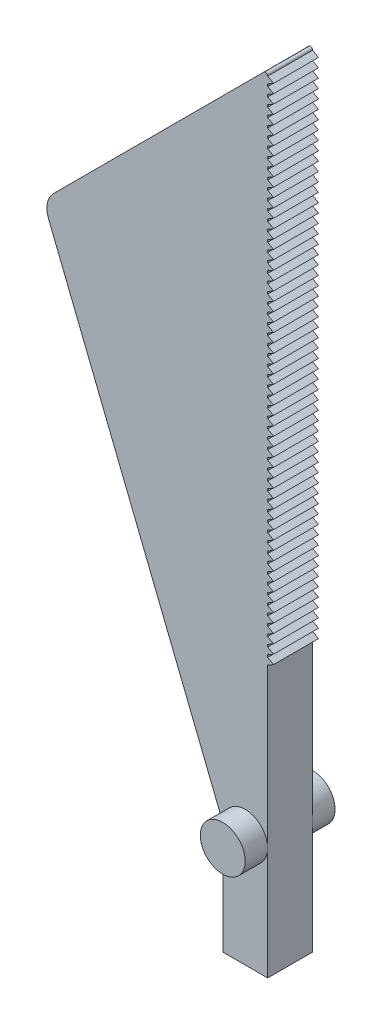
SolidWorks part; units mm, degrees
ref_plane "Front Plane" through (0, 0, 0) normal (0, 0, 1) x (1, 0, 0)
ref_plane "Top Plane" through (0, 0, 0) normal (0, 1, 0) x (1, 0, 0)
ref_plane "Right Plane" through (0, 0, 0) normal (1, 0, 0) x (0, 0, -1)
sketch "Sketch1" plane through (0, 0, 0) normal (0, 0, 1) x (1, 0, 0)
  circle A0 centre (0, 0) radius 2.54
  dimension "D1" = 5.08
extrude "Boss-Extrude1" add sketch "Sketch1" along normal mid plane 10.16
sketch "Sketch2" plane through (0, 0, 0) normal (0, 0, 1) x (1, 0, 0)
  line L0 (0, 0) -> (0, 76.2) construction
  line L1 (2.54, 0) -> (2.54, 75.5868)
  line L2 (2.1064, 75.7664) -> (-21.6757, 51.9843)
  line L4 (-2.54, -12.7) -> (2.54, -12.7)
  line L5 (2.54, -12.7) -> (2.54, 0)
  line L6 (-22.238, 49.2449) -> (-2.54, 0)
  line L7 (-2.54, 0) -> (-2.54, -12.7)
  circle A0 centre (0, 0) radius 2.54 construction
  arc A1 (-21.6757, 51.9843) -> (-22.238, 49.2449) centre (-19.8796, 50.1883) ccw
  arc A2 (2.54, 75.5868) -> (2.1064, 75.7664) centre (2.286, 75.5868) ccw
  point P19 (-22.86, 50.8)
  point P22 (2.54, 76.2)
  dimension "D4" = 2.54
  dimension "D5" = 0.254
  dimension "D1" = 76.2
  dimension "D2" = 25.4
  dimension "D3" = 50.8
  dimension "D6" = 12.7
extrude "Boss-Extrude2" add sketch "Sketch2" along normal mid plane 5.08
sketch "Sketch3" plane through (0, 0, 0) normal (0, 0, 1) x (1, 0, 0)
  line L0 (2.54, 75.5868) -> (3.1999, 75.2058)
  line L1 (3.1999, 75.2058) -> (2.54, 74.8248)
  line L2 (2.54, 0) -> (2.54, 75.5868) construction
  line L3 (2.54, 74.8248) -> (2.54, 75.5868)
  line L4 (2.54, 74.5708) -> (3.1999, 74.1898)
  line L5 (3.1999, 74.1898) -> (2.54, 73.8088)
  line L6 (2.54, 73.8088) -> (2.54, 74.5708)
  line L7 (2.54, 73.5548) -> (3.1999, 73.1738)
  line L8 (3.1999, 73.1738) -> (2.54, 72.7928)
  line L9 (2.54, 72.7928) -> (2.54, 73.5548)
  line L10 (2.54, 72.5388) -> (3.1999, 72.1578)
  line L11 (3.1999, 72.1578) -> (2.54, 71.7768)
  line L12 (2.54, 71.7768) -> (2.54, 72.5388)
  line L13 (2.54, 71.5228) -> (3.1999, 71.1418)
  line L14 (3.1999, 71.1418) -> (2.54, 70.7608)
  line L15 (2.54, 70.7608) -> (2.54, 71.5228)
  line L16 (2.54, 70.5068) -> (3.1999, 70.1258)
  line L17 (3.1999, 70.1258) -> (2.54, 69.7448)
  line L18 (2.54, 69.7448) -> (2.54, 70.5068)
  line L19 (2.54, 69.4908) -> (3.1999, 69.1098)
  line L20 (3.1999, 69.1098) -> (2.54, 68.7288)
  line L21 (2.54, 68.7288) -> (2.54, 69.4908)
  line L22 (2.54, 68.4748) -> (3.1999, 68.0938)
  line L23 (3.1999, 68.0938) -> (2.54, 67.7128)
  line L24 (2.54, 67.7128) -> (2.54, 68.4748)
  line L25 (2.54, 67.4588) -> (3.1999, 67.0778)
  line L26 (3.1999, 67.0778) -> (2.54, 66.6968)
  line L27 (2.54, 66.6968) -> (2.54, 67.4588)
  line L28 (2.54, 66.4428) -> (3.1999, 66.0618)
  line L29 (3.1999, 66.0618) -> (2.54, 65.6808)
  line L30 (2.54, 65.6808) -> (2.54, 66.4428)
  line L31 (2.54, 65.4268) -> (3.1999, 65.0458)
  line L32 (3.1999, 65.0458) -> (2.54, 64.6648)
  line L33 (2.54, 64.6648) -> (2.54, 65.4268)
  line L34 (2.54, 64.4108) -> (3.1999, 64.0298)
  line L35 (3.1999, 64.0298) -> (2.54, 63.6488)
  line L36 (2.54, 63.6488) -> (2.54, 64.4108)
  line L37 (2.54, 63.3948) -> (3.1999, 63.0138)
  line L38 (3.1999, 63.0138) -> (2.54, 62.6328)
  line L39 (2.54, 62.6328) -> (2.54, 63.3948)
  line L40 (2.54, 62.3788) -> (3.1999, 61.9978)
  line L41 (3.1999, 61.9978) -> (2.54, 61.6168)
  line L42 (2.54, 61.6168) -> (2.54, 62.3788)
  line L43 (2.54, 61.3628) -> (3.1999, 60.9818)
  line L44 (3.1999, 60.9818) -> (2.54, 60.6008)
  line L45 (2.54, 60.6008) -> (2.54, 61.3628)
  line L46 (2.54, 60.3468) -> (3.1999, 59.9658)
  line L47 (3.1999, 59.9658) -> (2.54, 59.5848)
  line L48 (2.54, 59.5848) -> (2.54, 60.3468)
  line L49 (2.54, 59.3308) -> (3.1999, 58.9498)
  line L50 (3.1999, 58.9498) -> (2.54, 58.5688)
  line L51 (2.54, 58.5688) -> (2.54, 59.3308)
  line L52 (2.54, 58.3148) -> (3.1999, 57.9338)
  line L53 (3.1999, 57.9338) -> (2.54, 57.5528)
  line L54 (2.54, 57.5528) -> (2.54, 58.3148)
  line L55 (2.54, 57.2988) -> (3.1999, 56.9178)
  line L56 (3.1999, 56.9178) -> (2.54, 56.5368)
  line L57 (2.54, 56.5368) -> (2.54, 57.2988)
  line L58 (2.54, 56.2828) -> (3.1999, 55.9018)
  line L59 (3.1999, 55.9018) -> (2.54, 55.5208)
  line L60 (2.54, 55.5208) -> (2.54, 56.2828)
  line L61 (2.54, 55.2668) -> (3.1999, 54.8858)
  line L62 (3.1999, 54.8858) -> (2.54, 54.5048)
  line L63 (2.54, 54.5048) -> (2.54, 55.2668)
  line L64 (2.54, 54.2508) -> (3.1999, 53.8698)
  line L65 (3.1999, 53.8698) -> (2.54, 53.4888)
  line L66 (2.54, 53.4888) -> (2.54, 54.2508)
  line L67 (2.54, 53.2348) -> (3.1999, 52.8538)
  line L68 (3.1999, 52.8538) -> (2.54, 52.4728)
  line L69 (2.54, 52.4728) -> (2.54, 53.2348)
  line L70 (2.54, 52.2188) -> (3.1999, 51.8378)
  line L71 (3.1999, 51.8378) -> (2.54, 51.4568)
  line L72 (2.54, 51.4568) -> (2.54, 52.2188)
  line L73 (2.54, 51.2028) -> (3.1999, 50.8218)
  line L74 (3.1999, 50.8218) -> (2.54, 50.4408)
  line L75 (2.54, 50.4408) -> (2.54, 51.2028)
  line L76 (2.54, 50.1868) -> (3.1999, 49.8058)
  line L77 (3.1999, 49.8058) -> (2.54, 49.4248)
  line L78 (2.54, 49.4248) -> (2.54, 50.1868)
  line L79 (2.54, 49.1708) -> (3.1999, 48.7898)
  line L80 (3.1999, 48.7898) -> (2.54, 48.4088)
  line L81 (2.54, 48.4088) -> (2.54, 49.1708)
  line L82 (2.54, 48.1548) -> (3.1999, 47.7738)
  line L83 (3.1999, 47.7738) -> (2.54, 47.3928)
  line L84 (2.54, 47.3928) -> (2.54, 48.1548)
  line L85 (2.54, 47.1388) -> (3.1999, 46.7578)
  line L86 (3.1999, 46.7578) -> (2.54, 46.3768)
  line L87 (2.54, 46.3768) -> (2.54, 47.1388)
  line L88 (2.54, 46.1228) -> (3.1999, 45.7418)
  line L89 (3.1999, 45.7418) -> (2.54, 45.3608)
  line L90 (2.54, 45.3608) -> (2.54, 46.1228)
  line L91 (2.54, 45.1068) -> (3.1999, 44.7258)
  line L92 (3.1999, 44.7258) -> (2.54, 44.3448)
  line L93 (2.54, 44.3448) -> (2.54, 45.1068)
  line L94 (2.54, 44.0908) -> (3.1999, 43.7098)
  line L95 (3.1999, 43.7098) -> (2.54, 43.3288)
  line L96 (2.54, 43.3288) -> (2.54, 44.0908)
  line L97 (2.54, 43.0748) -> (3.1999, 42.6938)
  line L98 (3.1999, 42.6938) -> (2.54, 42.3128)
  line L99 (2.54, 42.3128) -> (2.54, 43.0748)
  line L100 (2.54, 42.0588) -> (3.1999, 41.6778)
  line L101 (3.1999, 41.6778) -> (2.54, 41.2968)
  line L102 (2.54, 41.2968) -> (2.54, 42.0588)
  line L103 (2.54, 41.0428) -> (3.1999, 40.6618)
  line L104 (3.1999, 40.6618) -> (2.54, 40.2808)
  line L105 (2.54, 40.2808) -> (2.54, 41.0428)
  line L106 (2.54, 40.0268) -> (3.1999, 39.6458)
  line L107 (3.1999, 39.6458) -> (2.54, 39.2648)
  line L108 (2.54, 39.2648) -> (2.54, 40.0268)
  line L109 (2.54, 39.0108) -> (3.1999, 38.6298)
  line L110 (3.1999, 38.6298) -> (2.54, 38.2488)
  line L111 (2.54, 38.2488) -> (2.54, 39.0108)
  line L112 (2.54, 37.9948) -> (3.1999, 37.6138)
  line L113 (3.1999, 37.6138) -> (2.54, 37.2328)
  line L114 (2.54, 37.2328) -> (2.54, 37.9948)
  line L115 (2.54, 36.9788) -> (3.1999, 36.5978)
  line L116 (3.1999, 36.5978) -> (2.54, 36.2168)
  line L117 (2.54, 36.2168) -> (2.54, 36.9788)
  line L118 (2.54, 35.9628) -> (3.1999, 35.5818)
  line L119 (3.1999, 35.5818) -> (2.54, 35.2008)
  line L120 (2.54, 35.2008) -> (2.54, 35.9628)
  line L121 (2.54, 34.9468) -> (3.1999, 34.5658)
  line L122 (3.1999, 34.5658) -> (2.54, 34.1848)
  line L123 (2.54, 34.1848) -> (2.54, 34.9468)
  line L124 (2.54, 33.9308) -> (3.1999, 33.5498)
  line L125 (3.1999, 33.5498) -> (2.54, 33.1688)
  line L126 (2.54, 33.1688) -> (2.54, 33.9308)
  line L127 (2.54, 32.9148) -> (3.1999, 32.5338)
  line L128 (3.1999, 32.5338) -> (2.54, 32.1528)
  line L129 (2.54, 32.1528) -> (2.54, 32.9148)
  line L130 (2.54, 31.8988) -> (3.1999, 31.5178)
  line L131 (3.1999, 31.5178) -> (2.54, 31.1368)
  line L132 (2.54, 31.1368) -> (2.54, 31.8988)
  line L133 (2.54, 30.8828) -> (3.1999, 30.5018)
  line L134 (3.1999, 30.5018) -> (2.54, 30.1208)
  line L135 (2.54, 30.1208) -> (2.54, 30.8828)
  line L136 (2.54, 29.8668) -> (3.1999, 29.4858)
  line L137 (3.1999, 29.4858) -> (2.54, 29.1048)
  line L138 (2.54, 29.1048) -> (2.54, 29.8668)
  line L139 (2.54, 28.8508) -> (3.1999, 28.4698)
  line L140 (3.1999, 28.4698) -> (2.54, 28.0888)
  line L141 (2.54, 28.0888) -> (2.54, 28.8508)
  line L142 (2.54, 27.8348) -> (3.1999, 27.4538)
  line L143 (3.1999, 27.4538) -> (2.54, 27.0728)
  line L144 (2.54, 27.0728) -> (2.54, 27.8348)
  line L145 (2.54, 26.8188) -> (3.1999, 26.4378)
  line L146 (3.1999, 26.4378) -> (2.54, 26.0568)
  line L147 (2.54, 26.0568) -> (2.54, 26.8188)
  line L148 (2.54, 25.8028) -> (3.1999, 25.4218)
  line L149 (3.1999, 25.4218) -> (2.54, 25.0408)
  line L150 (2.54, 25.0408) -> (2.54, 25.8028)
  line L151 (2.54, 24.7868) -> (3.1999, 24.4058)
  line L152 (3.1999, 24.4058) -> (2.54, 24.0248)
  line L153 (2.54, 24.0248) -> (2.54, 24.7868)
  line L154 (2.54, 23.7708) -> (3.1999, 23.3898)
  line L155 (3.1999, 23.3898) -> (2.54, 23.0088)
  line L156 (2.54, 23.0088) -> (2.54, 23.7708)
  line L157 (2.54, 22.7548) -> (3.1999, 22.3738)
  line L158 (3.1999, 22.3738) -> (2.54, 21.9928)
  line L159 (2.54, 21.9928) -> (2.54, 22.7548)
  line L160 (2.54, 21.7388) -> (3.1999, 21.3578)
  line L161 (3.1999, 21.3578) -> (2.54, 20.9768)
  line L162 (2.54, 20.9768) -> (2.54, 21.7388)
  line L163 (2.54, 20.7228) -> (3.1999, 20.3418)
  line L164 (3.1999, 20.3418) -> (2.54, 19.9608)
  line L165 (2.54, 19.9608) -> (2.54, 20.7228)
  line L166 (2.54, 19.7068) -> (3.1999, 19.3258)
  line L167 (3.1999, 19.3258) -> (2.54, 18.9448)
  line L168 (2.54, 18.9448) -> (2.54, 19.7068)
  line L169 (2.54, 18.6908) -> (3.1999, 18.3098)
  line L170 (3.1999, 18.3098) -> (2.54, 17.9288)
  line L171 (2.54, 17.9288) -> (2.54, 18.6908)
  dimension "D1" = 0.762
  dimension "D2" = 57
extrude "Boss-Extrude3" add sketch "Sketch3" along normal mid plane 5.08
sketch "Sketch4" plane through (0, 0, -5.08) normal (0, 0, -1) x (-1, 0, 0)
  point P0 (0, 0)
